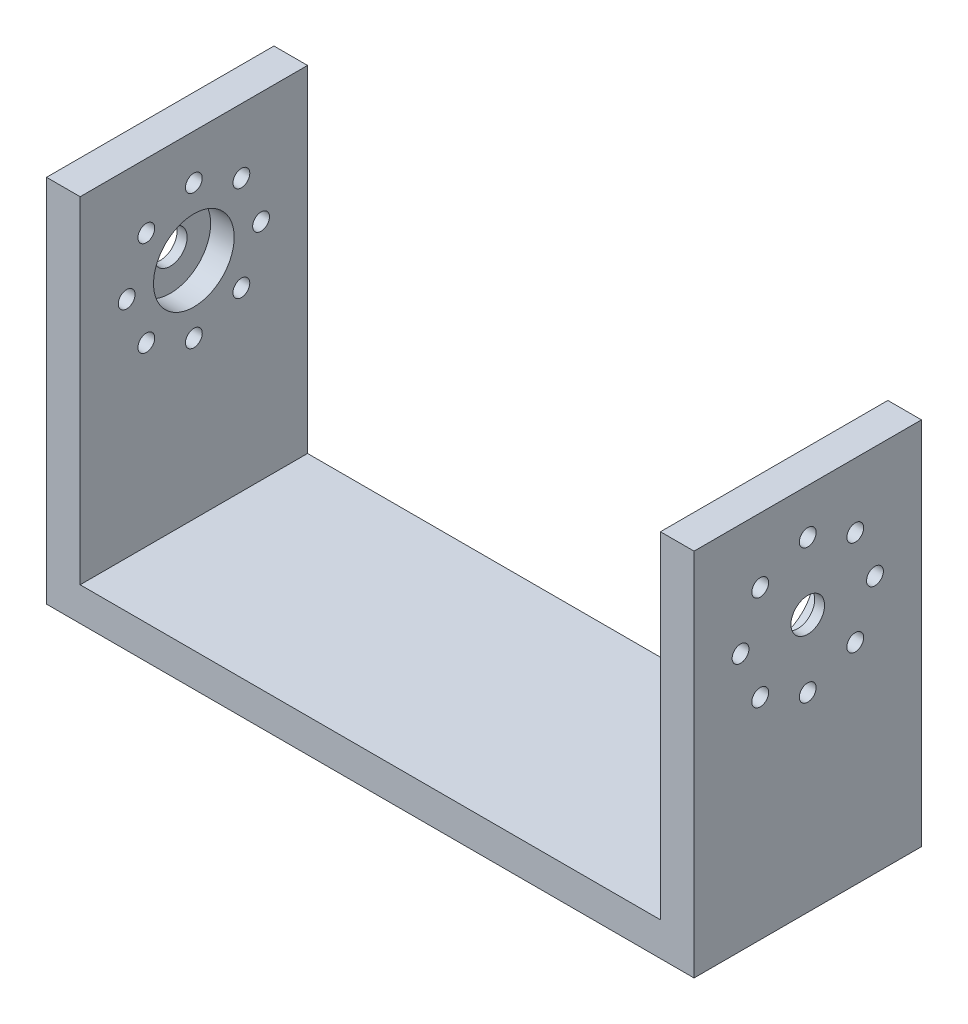
SolidWorks part; units mm, degrees
ref_plane "Front Plane" through (0, 0, 0) normal (0, 0, 1) x (1, 0, 0)
ref_plane "Top Plane" through (0, 0, 0) normal (0, 1, 0) x (1, 0, 0)
ref_plane "Right Plane" through (0, 0, 0) normal (1, 0, 0) x (0, 0, -1)
sketch "Sketch1" plane through (0, 0, 0) normal (0, 1, 0) x (1, 0, 0)
  line L1 (0, 0) -> (57.8, 0)
  line L2 (0, 0) -> (0, 20.3)
  line L3 (0, 20.3) -> (57.8, 20.3)
  line L4 (57.8, 0) -> (57.8, 20.3)
  dimension "D1" = 57.8
  dimension "D2" = 20.3
extrude "YawMount" add sketch "Sketch1" along normal blind 3
sketch "Sketch2" plane through (0, 3, 0) normal (0, 1, 0) x (1, 0, 0)
  line L0 (0, 0) -> (57.8, 0) construction
  line L1 (0, 20.3) -> (3, 20.3)
  line L2 (0, 20.3) -> (0, 0)
  line L3 (0, 0) -> (3, 0)
  line L4 (3, 20.3) -> (3, 0)
  line L6 (57.8, 20.3) -> (54.8, 20.3)
  line L7 (57.8, 20.3) -> (57.8, 0)
  line L8 (57.8, 0) -> (54.8, 0)
  line L9 (54.8, 20.3) -> (54.8, 0)
  dimension "D1" = 3
  dimension "D2" = 3
extrude "BodyConnectors" add sketch "Sketch2" along normal blind 30
sketch "Sketch3" plane through (57.8, 0, 0) normal (1, 0, 0) x (0, 0, -1)
  line L0 (0, 33) -> (20.3, 33) construction
  circle A0 centre (10.15, 23) radius 1.5
  circle A1 centre (16.15, 23) radius 0.75
  circle A2 centre (14.3926, 18.7574) radius 0.75
  circle A3 centre (10.15, 17) radius 0.75
  circle A4 centre (5.9074, 18.7574) radius 0.75
  circle A5 centre (4.15, 23) radius 0.75
  circle A6 centre (5.9074, 27.2426) radius 0.75
  circle A7 centre (10.15, 29) radius 0.75
  circle A8 centre (14.3926, 27.2426) radius 0.75
  point P4 (10.15, 33)
  point P9 (0, 0)
  point P10 (0, 0)
  point P24 (10.15, 23)
  point P25 (10.15, 25)
  dimension "D1" = 3
  dimension "D2" = 1.5
  dimension "D3" = 20
  dimension "D4" = 6
  dimension "D5" = 8
extrude "Axle-Mounts" cut sketch "Sketch3" against normal up to surface (57.8 mm away) up to face at (0, 16.5, -10.15)
sketch "Sketch4" plane through (54.8, 0, 0) normal (-1, 0, 0) x (0, 0, 1)
  circle A0 centre (-10.15, 23) radius 3.6
  circle A1 centre (-10.15, 23) radius 1.5 construction
  dimension "D1" = 7.2
extrude "Slide-Counterbore" cut sketch "Sketch4" against normal blind 2.12
sketch "Sketch5" plane through (3, 0, 0) normal (1, 0, 0) x (0, 0, -1)
  circle A0 centre (10.15, 23) radius 3.6
  circle A1 centre (10.15, 23) radius 1.5 construction
  dimension "D1" = 7.2
extrude "Gear-Counterbore" cut sketch "Sketch5" against normal blind 2.1
equation "\"srv_w\"= 40.43mm'width of Sain Smart SR319"
equation "\"D1@Sketch1\"=51.8mm + \"mnt_thick\"*2"
equation "\"srv_h\"= 40.61mm'height of Sain Smart SR319"
equation "\"srv_d\"= 20.3mm'depth of Sain Smart SR319"
equation "\"D2@Sketch1\"=\"srv_d\""
equation "\"mnt_thick\"= 3mm'thickness of bracket"
equation "\"D1@YawMount\" = \"mnt_thick\""
equation "\"D2@Sketch2\"=\"mnt_thick\""
equation "\"D1@Sketch2\"=\"mnt_thick\""
